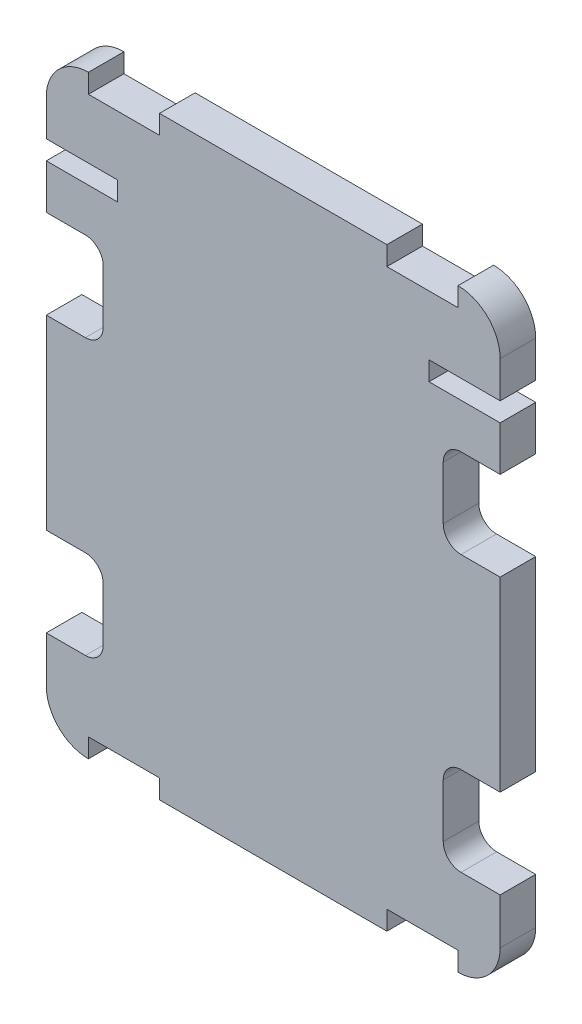
SolidWorks part; units mm, degrees
ref_plane "Front Plane" through (0, 0, 0) normal (0, 0, 1) x (1, 0, 0)
ref_plane "Top Plane" through (0, 0, 0) normal (0, 1, 0) x (1, 0, 0)
ref_plane "Right Plane" through (0, 0, 0) normal (1, 0, 0) x (0, 0, -1)
sketch "Sketch1" plane through (0, 0, 0) normal (0, 0, 1) x (1, 0, 0)
  line L0 (8662.2074, 3006.6966) -> (8662.2074, 3000.1668)
  line L1 (8662.2074, 2996.7632) -> (8662.2074, 2988.7876)
  line L2 (8662.2074, 2972.9126) -> (8662.2074, 2939.6533)
  line L3 (8662.2074, 2923.7783) -> (8662.2074, 2915.5741)
  line L4 (8641.989, 2908.0557) -> (8601.3998, 2908.0557)
  line L5 (8654.689, 2911.4593) -> (8641.989, 2911.4593)
  line L6 (8601.3998, 2911.4593) -> (8588.6998, 2911.4593)
  line L7 (8581.1814, 2915.5741) -> (8581.1814, 2923.7783)
  line L8 (8581.1814, 2939.6533) -> (8581.1814, 2972.9126)
  line L9 (8581.1814, 2988.7876) -> (8581.1814, 2996.7632)
  line L10 (8581.1814, 3000.1668) -> (8581.1814, 3006.6966)
  line L11 (8601.3998, 3014.215) -> (8641.989, 3014.215)
  line L12 (8588.6998, 3010.8114) -> (8601.3998, 3010.8114)
  line L13 (8641.989, 3010.8114) -> (8654.689, 3010.8114)
  line L14 (8662.2074, 2939.6533) -> (8655.2224, 2939.6533)
  line L15 (8662.2074, 2923.7783) -> (8655.2224, 2923.7783)
  line L16 (8652.0474, 2936.4783) -> (8652.0474, 2926.9533)
  line L17 (8581.1814, 2939.6533) -> (8588.1664, 2939.6533)
  line L18 (8581.1814, 2923.7783) -> (8588.1664, 2923.7783)
  line L19 (8591.3414, 2936.4783) -> (8591.3414, 2926.9533)
  line L20 (8662.2074, 2972.9126) -> (8655.2224, 2972.9126)
  line L21 (8662.2074, 2988.7876) -> (8655.2224, 2988.7876)
  line L22 (8652.0474, 2976.0876) -> (8652.0474, 2985.6126)
  line L23 (8581.1814, 2972.9126) -> (8588.1664, 2972.9126)
  line L24 (8581.1814, 2988.7876) -> (8588.1664, 2988.7876)
  line L25 (8591.3414, 2976.0876) -> (8591.3414, 2985.6126)
  line L26 (8588.6998, 2911.4593) -> (8588.6998, 2908.0557)
  line L27 (8601.3998, 2911.4593) -> (8601.3998, 2908.0557)
  line L28 (8654.689, 2911.4593) -> (8654.689, 2908.0557)
  line L29 (8641.989, 2911.4593) -> (8641.989, 2908.0557)
  line L30 (8593.8814, 2996.7632) -> (8593.8814, 3000.1668)
  line L31 (8649.5074, 2996.7632) -> (8649.5074, 3000.1668)
  line L32 (8581.1814, 3000.1668) -> (8593.8814, 3000.1668)
  line L33 (8581.1814, 2996.7632) -> (8593.8814, 2996.7632)
  line L34 (8649.5074, 3000.1668) -> (8662.2074, 3000.1668)
  line L35 (8649.5074, 2996.7632) -> (8662.2074, 2996.7632)
  line L36 (8588.6998, 3014.215) -> (8588.6998, 3010.8114)
  line L37 (8601.3998, 3014.215) -> (8601.3998, 3010.8114)
  line L38 (8654.689, 3014.215) -> (8654.689, 3010.8114)
  line L39 (8641.989, 3014.215) -> (8641.989, 3010.8114)
  arc A0 (8662.2074, 3006.6966) -> (8654.689, 3014.215) centre (8654.689, 3006.6966) ccw
  arc A1 (8654.689, 2908.0557) -> (8662.2074, 2915.5741) centre (8654.689, 2915.5741) ccw
  arc A2 (8581.1814, 2915.5741) -> (8588.6998, 2908.0557) centre (8588.6998, 2915.5741) ccw
  arc A3 (8588.6998, 3014.215) -> (8581.1814, 3006.6966) centre (8588.6998, 3006.6966) ccw
  arc A4 (8652.0474, 2926.9533) -> (8655.2224, 2923.7783) centre (8655.2224, 2926.9533) ccw
  arc A5 (8655.2224, 2939.6533) -> (8652.0474, 2936.4783) centre (8655.2224, 2936.4783) ccw
  arc A6 (8588.1664, 2923.7783) -> (8591.3414, 2926.9533) centre (8588.1664, 2926.9533) ccw
  arc A7 (8591.3414, 2936.4783) -> (8588.1664, 2939.6533) centre (8588.1664, 2936.4783) ccw
  arc A8 (8655.2224, 2988.7876) -> (8652.0474, 2985.6126) centre (8655.2224, 2985.6126) ccw
  arc A9 (8652.0474, 2976.0876) -> (8655.2224, 2972.9126) centre (8655.2224, 2976.0876) ccw
  arc A10 (8591.3414, 2985.6126) -> (8588.1664, 2988.7876) centre (8588.1664, 2985.6126) ccw
  arc A11 (8588.1664, 2972.9126) -> (8591.3414, 2976.0876) centre (8588.1664, 2976.0876) ccw
extrude "Boss-Extrude1" add sketch "Sketch1" along normal blind 6.35
